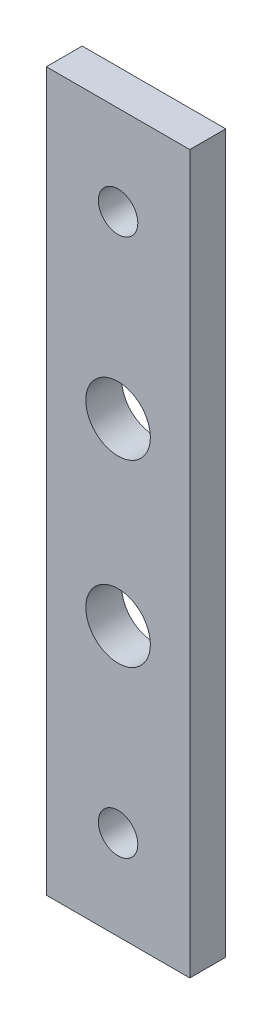
SolidWorks part; units mm, degrees
ref_plane "Plan de face" through (0, 0, 0) normal (0, 0, 1) x (1, 0, 0)
ref_plane "Plan de dessus" through (0, 0, 0) normal (0, 1, 0) x (1, 0, 0)
ref_plane "Plan de droite" through (0, 0, 0) normal (1, 0, 0) x (0, 0, -1)
sketch "Esquisse1" plane through (0, 0, 0) normal (0, 0, 1) x (1, 0, 0)
  line L0 (0, 50) -> (20, 50) construction
  line L1 (0, 0) -> (20, 0)
  line L2 (0, 0) -> (0, 100)
  line L3 (0, 100) -> (20, 100)
  line L4 (20, 0) -> (20, 100)
  line L5 (0, 37.5) -> (20, 37.5) construction
  line L6 (0, 12.5) -> (20, 12.5) construction
  line L8 (14, 85.1906) -> (14, 89.8094)
  line L9 (14, 89.8094) -> (10, 92.1188)
  line L10 (10, 92.1188) -> (6, 89.8094)
  line L11 (6, 89.8094) -> (6, 85.1906)
  line L12 (6, 85.1906) -> (10, 82.8812)
  line L13 (10, 82.8812) -> (14, 85.1906)
  line L14 (14, 10.1906) -> (14, 14.8094)
  line L15 (14, 14.8094) -> (10, 17.1188)
  line L16 (10, 17.1188) -> (6, 14.8094)
  line L17 (6, 14.8094) -> (6, 10.1906)
  line L18 (6, 10.1906) -> (10, 7.8812)
  line L19 (10, 7.8812) -> (14, 10.1906)
  circle A0 centre (10, 37.5) radius 2.75
  circle A1 centre (10, 12.5) radius 2.75
  circle A2 centre (10, 87.5) radius 2.75
  circle A3 centre (10, 62.5) radius 2.75
  circle A4 centre (10, 62.5) radius 4.5
  circle A5 centre (10, 37.5) radius 4.5
  circle A6 centre (10, 87.5) radius 4 construction
  circle A7 centre (10, 12.5) radius 4 construction
  point P12 (10, 37.5)
  dimension "D5" = 5.5
  dimension "D6" = 9
  dimension "D1" = 20
  dimension "D2" = 12.5
  dimension "D3" = 25
  dimension "D4" = 12.5
  dimension "D7" = 8
extrude "Boss.-Extru.2" add sketch "Esquisse1" against normal blind 5 contours L1 L4 L3 L2 A5 A4 L13 L12 L11 L10 L9 L8 L19 L18 L17 L16 L15 L14 | L12 L13 L8 L9 L10 L11 A2 | L18 L19 L14 L15 L16 L17 A1
